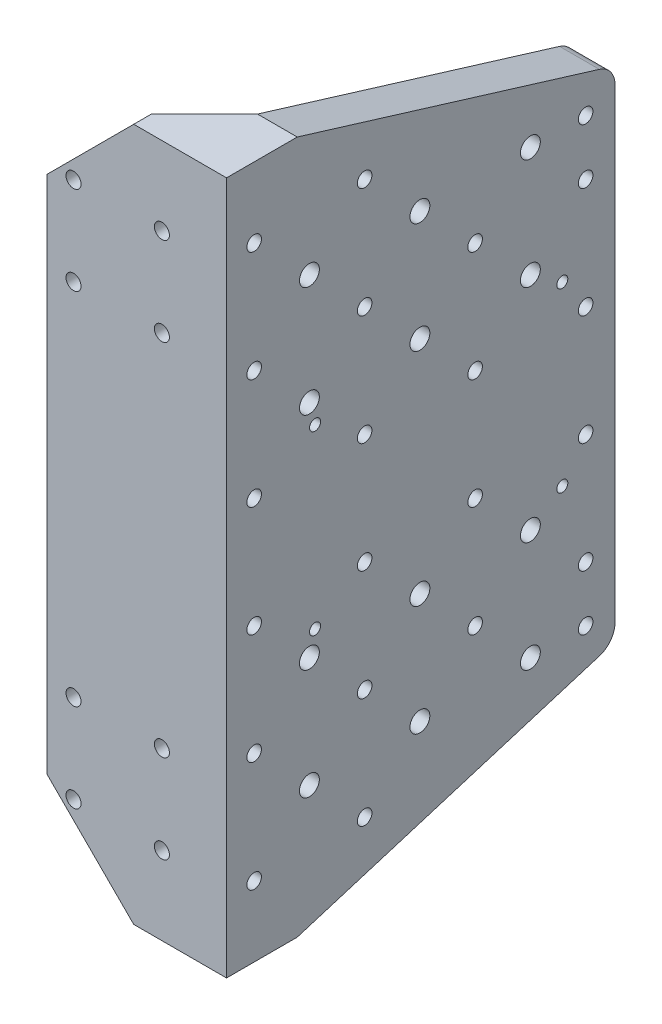
SolidWorks part; units mm, degrees
ref_plane "Plan de face" through (0, 0, 0) normal (0, 0, 1) x (1, 0, 0)
ref_plane "Plan de dessus" through (0, 0, 0) normal (0, 1, 0) x (1, 0, 0)
ref_plane "Plan de droite" through (0, 0, 0) normal (1, 0, 0) x (0, 0, -1)
sketch "Esquisse1" plane through (0, 0, 0) normal (0, 0, 1) x (1, 0, 0)
  line L0 (-13.5, -16.2) -> (-13.5, 16.2) construction
  line L1 (-16, -27.7) -> (24.625, -27.7)
  line L2 (-16, -27.7) -> (-16, 129.1)
  line L3 (-16, 129.1) -> (24.625, 129.1)
  line L4 (24.625, -27.7) -> (24.625, 129.1)
  line L7 (19.625, 26.7) -> (19.625, 74.7) construction
  line L8 (12, -22.7) -> (-12, -22.7) construction
  line L9 (-12, 124.1) -> (12, 124.1) construction
  point P4 (25.8016, 115.4284)
  point P5 (-16.4047, -21.2392)
  point P8 (-16, -28.146)
  dimension "D1" = 2.5
  dimension "D2" = 5
  dimension "D3" = 5
  dimension "D4" = 5
extrude "Boss.-Extru.1" add sketch "Esquisse1" along normal blind 4
sketch "Esquisse2" plane through (0, 0, 0) normal (0, 0, -1) x (-1, 0, 0)
  line L0 (16, -27.7) -> (-24.625, -27.7) construction
  line L1 (-24.625, 129.1) -> (-15.625, 129.1)
  line L2 (-24.625, 129.1) -> (-24.625, -27.7)
  line L3 (-24.625, -27.7) -> (-15.625, -27.7)
  line L4 (-15.625, 129.1) -> (-15.625, -27.7)
  dimension "D1" = 9
extrude "Boss.-Extru.2" add sketch "Esquisse2" along normal up to surface (83.9 mm away)
sketch "Esquisse3" plane through (15.625, 0, 0) normal (-1, 0, 0) x (0, 0, 1)
  line L0 (-83.9, 129.1) -> (-83.9, -27.7) construction
  line L1 (-83.9, 75.7) -> (-3.5, 75.7)
  line L2 (-83.9, 75.7) -> (-83.9, 25.7)
  line L3 (-83.9, 25.7) -> (-3.5, 25.7)
  line L4 (-3.5, 75.7) -> (-3.5, 25.7)
  line L5 (0, 50.7) -> (-3.5, 50.7) construction
  line L6 (0, -27.7) -> (0, 129.1) construction
  point P6 (0, 0)
  dimension "D1" = 50
  dimension "D2" = 3.5
extrude "Enlèv. mat.-Extru.1" cut sketch "Esquisse3" against normal blind 4
fillet "Congé1" radius 5 2 edges at (17.625, 25.7, -3.5) (17.625, 75.7, -3.5)
sketch "Esquisse4" plane through (0, 0, 4) normal (0, 0, 1) x (1, 0, 0)
  line L0 (10, 10) -> (-10, 10) construction
  line L5 (10, 10) -> (10, -10) construction
  line L6 (10, -10) -> (-10, -10) construction
  line L7 (-10, 10) -> (-10, -10) construction
  point P4 (-4.7782, 2.5691)
  point P5 (-7.7202, -4.5843)
  point P6 (-8.3566, -4.0265)
  point P7 (-10, -10)
  dimension "D1" = 20
  dimension "D2" = 20
hole_wizard "Dégagement M31" positions "Esquisse5" profile "Esquisse7" hole size "M3" standard "Ansi Metric" end condition through all
sketch "Esquisse5" plane through (0, 0, 4) normal (0, 0, 1) x (1, 0, 0)
  point P0 (-10, -10)
  point P3 (-10, 10)
  point P6 (10, 10)
  point P9 (10, -10)
sketch "Esquisse7" plane through (-10, -10, 4) normal (1, 0, 0) x (0, -1, 0)
  line L0 (0, 0) -> (0, 87.9)
  line L1 (0, 87.9) -> (1.7, 87.9)
  line L2 (1.7, 87.9) -> (1.7, 0)
  line L5 (1.7, 0) -> (0, 0)
  line L11 (0, -6.35) -> (0, 107.95) construction
  dimension "Diamètre du perçage jusqu'au prochain" = 3.4
  dimension "Profondeur du perçage jusqu'au prochain" = 87.9
ref_plane "Plan1" through (0, 50.7, 0) normal (0, 1, 0) x (1, 0, 0)
mirror "Symétrie1" about plane through (0, 50.7, 0) normal (0, 1, 0) of "Dégagement M31"
sketch "Esquisse8" plane through (0, 129.1, 0) normal (0, 1, 0) x (1, 0, 0)
  line L0 (3.625, 0) -> (15.625, 12)
  line L1 (15.625, 0) -> (-16, 0) construction
  line L2 (15.625, 83.9) -> (15.625, 0) construction
  line L3 (15.625, 12) -> (15.625, 0)
  line L4 (15.625, 0) -> (3.625, 0)
  dimension "D1" = 45
  dimension "D2" = 12
extrude "Boss.-Extru.3" add sketch "Esquisse8" against normal blind 4
sketch "Esquisse10" plane through (0, 0, 0) normal (0, 0, -1) x (-1, 0, 0)
  line L0 (-3.625, 129.1) -> (16, 109.475)
  line L1 (16, 129.1) -> (16, -27.7) construction
  line L2 (16, 109.475) -> (16, 129.1)
  line L3 (16, 129.1) -> (-3.625, 129.1)
extrude "Enlèv. mat.-Extru.2" cut sketch "Esquisse10" against normal through all
sketch "Esquisse11" plane through (24.625, 0, 0) normal (1, 0, 0) x (0, 0, -1)
  line L0 (83.9, 107.1) -> (12, 129.1)
  line L1 (83.9, -27.7) -> (83.9, 129.1) construction
  line L2 (-4, 129.1) -> (83.9, 129.1) construction
  line L3 (12, 129.1) -> (83.9, 129.1)
  line L4 (83.9, 129.1) -> (83.9, 107.1)
  point P8 (0, 0)
  dimension "D1" = 22
extrude "Enlèv. mat.-Extru.3" cut sketch "Esquisse11" against normal through all
sketch "Esquisse12" plane through (24.625, 0, 0) normal (1, 0, 0) x (0, 0, -1)
  line L0 (71.97, 70.7) -> (71.97, 30.7) construction
  line L1 (16.03, 70.7) -> (16.03, 30.7) construction
hole_wizard "Trou taraudé M3x0.51" positions "Esquisse3D1" profile "Esquisse13" tap size "M3x0.5" standard "Ansi Metric" end condition through all
sketch3d "Esquisse3D1"
  point P0 (24.625, 70.7, -71.97)
  point P3 (24.625, 30.7, -71.97)
  point P6 (24.625, 70.7, -16.03)
  point P9 (24.625, 30.7, -16.03)
sketch "Esquisse13" plane through (24.625, 70.7, -71.97) normal (0, 1, 0) x (0, 0, -1)
  line L0 (0, 0) -> (0, 40.625)
  line L1 (0, 40.625) -> (1.25, 40.625)
  line L2 (1.25, 40.625) -> (1.25, 0)
  line L5 (1.25, 0) -> (0, 0)
  line L11 (0, -6.35) -> (0, 107.95) construction
  dimension "Diamètre du trou pour taraudage jusqu'au prochain" = 2.5
  dimension "Profondeur du trou pour taraudage jusqu'au prochain" = 40.625
cosmetic thread "Filetage de perçage1" parameters "D2"=3
cosmetic thread "Filetage de perçage2" parameters "D2"=3
cosmetic thread "Filetage de perçage3" parameters "D2"=3
cosmetic thread "Filetage de perçage4" parameters "D2"=3
sketch "Esquisse14" plane through (24.625, 0, 0) normal (1, 0, 0) x (0, 0, -1)
  line L0 (-4, 50.7) -> (83.9, 50.7) construction
  line L1 (-4, -27.7) -> (-4, 129.1) construction
  line L3 (2.25, 63.2) -> (14.75, 63.2) construction
  line L4 (14.75, 63.2) -> (14.75, 75.7) construction
  point P4 (0, 0)
  dimension "D1" = 12.5
  dimension "D2" = 6.25
  dimension "D3" = 12.5
  dimension "D4" = 12.5
hole_wizard "Trou taraudé M4x0.71" positions "Esquisse3D2" profile "Esquisse15" tap size "M4x0.7" standard "Ansi Metric" end condition through all
sketch3d "Esquisse3D2"
  point P0 (24.625, 63.2, -2.25)
sketch "Esquisse15" plane through (24.625, 63.2, -2.25) normal (0, 1, 0) x (0, 0, -1)
  line L0 (0, 0) -> (0, 40.625)
  line L1 (0, 40.625) -> (1.65, 40.625)
  line L2 (1.65, 40.625) -> (1.65, 0)
  line L5 (1.65, 0) -> (0, 0)
  line L11 (0, -6.35) -> (0, 107.95) construction
  dimension "Diamètre du trou pour taraudage jusqu'au prochain" = 3.3
  dimension "Profondeur du trou pour taraudage jusqu'au prochain" = 40.625
cosmetic thread "Filetage de perçage5" parameters "D2"=4
pattern_linear "Répétition linéaire1" count 4 spacing 25 along (0, 0, -1) count 3 spacing 25 along (0, 1, 0) skipping (2, 2), (3, 2) of "Trou taraudé M4x0.71"
cosmetic thread "Filetage de perçage6" parameters "D2"=4
cosmetic thread "Filetage de perçage7" parameters "D2"=4
cosmetic thread "Filetage de perçage8" parameters "D2"=4
cosmetic thread "Filetage de perçage9" parameters "D2"=4
cosmetic thread "Filetage de perçage10" parameters "D2"=4
cosmetic thread "Filetage de perçage11" parameters "D2"=4
cosmetic thread "Filetage de perçage12" parameters "D2"=4
cosmetic thread "Filetage de perçage13" parameters "D2"=4
cosmetic thread "Filetage de perçage14" parameters "D2"=4
hole_wizard "Dégagement M42" positions "Esquisse3D3" profile "Esquisse17" hole size "M4" standard "Ansi Metric" end condition through all
sketch3d "Esquisse3D3"
  point P0 (24.625, 75.7, -14.75)
sketch "Esquisse17" plane through (24.625, 75.7, -14.75) normal (0, 1, 0) x (0, 0, -1)
  line L0 (0, 0) -> (0, 40.625)
  line L1 (0, 40.625) -> (2.25, 40.625)
  line L2 (2.25, 40.625) -> (2.25, 0)
  line L5 (2.25, 0) -> (0, 0)
  line L11 (0, -6.35) -> (0, 107.95) construction
  dimension "Diamètre du perçage jusqu'au prochain" = 4.5
  dimension "Profondeur du perçage jusqu'au prochain" = 40.625
pattern_linear "Répétition linéaire2" count 3 spacing 25 along (0, 0, -1) count 2 spacing 25 along (0, 1, 0) of "Dégagement M42"
sketch "Esquisse18" plane through (24.625, 0, 0) normal (1, 0, 0) x (0, 0, -1)
  line L0 (77.25, 88.2) -> (77.25, 100.7) construction
  line L1 (77.25, 100.7) -> (64.75, 100.7) construction
  point P5 (77.25, 100.7)
hole_wizard "Trou taraudé M4x0.72" positions "Esquisse3D4" profile "Esquisse19" tap size "M4x0.7" standard "Ansi Metric" end condition through all
sketch3d "Esquisse3D4"
  point P0 (24.625, 100.7, -77.25)
sketch "Esquisse19" plane through (24.625, 100.7, -77.25) normal (0, 1, 0) x (0, 0, -1)
  line L0 (0, 0) -> (0, 40.625)
  line L1 (0, 40.625) -> (1.65, 40.625)
  line L2 (1.65, 40.625) -> (1.65, 0)
  line L5 (1.65, 0) -> (0, 0)
  line L11 (0, -6.35) -> (0, 107.95) construction
  dimension "Diamètre du trou pour taraudage jusqu'au prochain" = 3.3
  dimension "Profondeur du trou pour taraudage jusqu'au prochain" = 40.625
cosmetic thread "Filetage de perçage15" parameters "D2"=4
mirror "Symétrie2" about plane through (0, 50.7, 0) normal (0, 1, 0) of "Répétition linéaire1", "Trou taraudé M4x0.72", "Répétition linéaire2", "Enlèv. mat.-Extru.2", "Boss.-Extru.3", "Enlèv. mat.-Extru.3", "Trou taraudé M4x0.71", "Dégagement M42"
fillet "Congé2" radius 5 2 edges at (20.125, -5.7, -83.9) (20.125, 107.1, -83.9)
